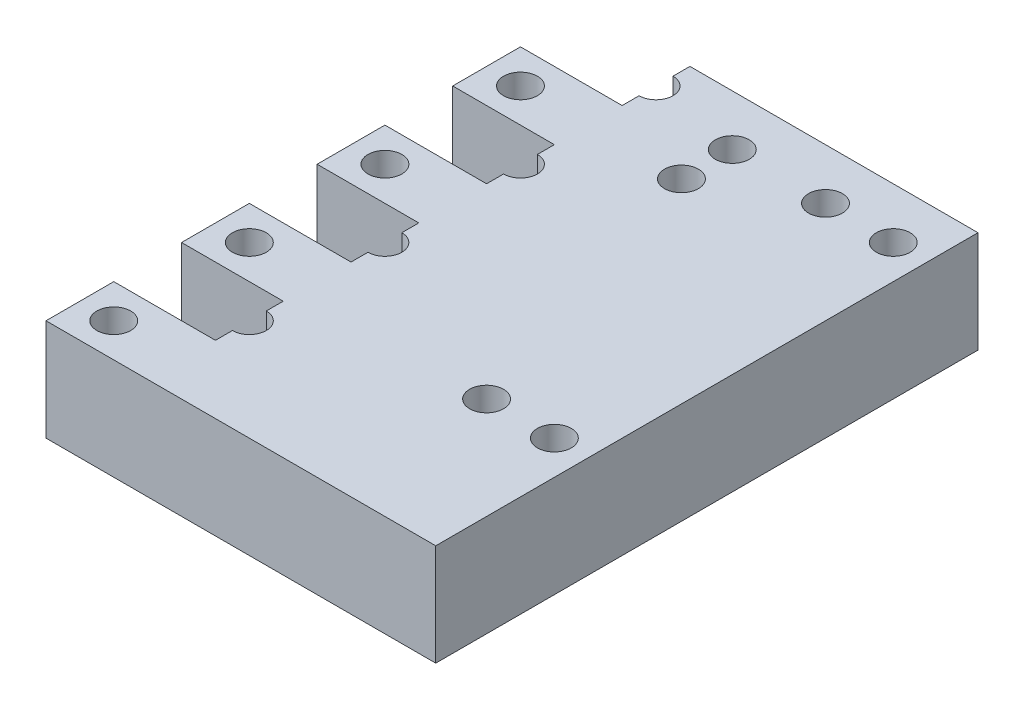
SolidWorks part; units mm, degrees
ref_plane "Front Plane" through (0, 0, 0) normal (0, 0, 1) x (1, 0, 0)
ref_plane "Top Plane" through (0, 0, 0) normal (0, 1, 0) x (1, 0, 0)
ref_plane "Right Plane" through (0, 0, 0) normal (1, 0, 0) x (0, 0, -1)
sketch "Sketch1" plane through (0, 0, 0) normal (0, 1, 0) x (1, 0, 0)
  line L0 (0, 0) -> (0, 4)
  line L1 (0, 4) -> (6, 4)
  line L2 (6, 4) -> (6, 8)
  line L3 (6, 8) -> (0, 8)
  line L4 (0, 8) -> (0, 12)
  line L5 (0, 12) -> (6, 12)
  line L6 (6, 12) -> (6, 16)
  line L7 (6, 16) -> (0, 16)
  line L8 (0, 16) -> (0, 20)
  line L9 (0, 20) -> (6, 20)
  line L10 (6, 20) -> (6, 24)
  line L11 (6, 24) -> (0, 24)
  line L12 (0, 24) -> (0, 28)
  line L13 (0, 28) -> (6, 28)
  line L14 (6, 28) -> (6, 32)
  line L15 (6, 32) -> (23, 32)
  line L16 (23, 32) -> (23, 0)
  line L17 (23, 0) -> (0, 0)
  dimension "D1" = 32
  dimension "D2" = 4
  dimension "D3" = 4
  dimension "D4" = 4
  dimension "D5" = 4
  dimension "D6" = 4
  dimension "D7" = 4
  dimension "D8" = 4
  dimension "D9" = 6
  dimension "D10" = 17
extrude "Boss-Extrude1" add sketch "Sketch1" along normal blind 6
sketch "Sketch2" plane through (0, 6, 0) normal (0, 1, 0) x (1, 0, 0)
  line L0 (0, 28) -> (0, 24) construction
  line L1 (0, 20) -> (0, 16) construction
  line L2 (0, 12) -> (0, 8) construction
  line L3 (0, 4) -> (0, 0) construction
  line L6 (6, 24) -> (6, 20) construction
  line L7 (6, 32) -> (6, 28) construction
  line L8 (6, 16) -> (6, 12) construction
  line L9 (6, 8) -> (6, 4) construction
  line L10 (23, 0) -> (23, 32) construction
  line L11 (0, 0) -> (23, 0) construction
  line L12 (23, 32) -> (6, 32) construction
  circle A0 centre (2, 26) radius 1
  circle A1 centre (2, 18) radius 1
  circle A2 centre (2, 10) radius 1
  circle A3 centre (2, 2) radius 1
  circle A4 centre (6, 22) radius 1
  circle A5 centre (6, 30) radius 1
  circle A6 centre (6, 14) radius 1
  circle A7 centre (6, 6) radius 1
  circle A8 centre (21, 29) radius 1
  circle A9 centre (21, 9) radius 1
  circle A10 centre (17, 29) radius 1
  circle A11 centre (17, 9) radius 1
  point P8 (0, 26)
  point P13 (0, 18)
  point P16 (0, 10)
  point P19 (0, 2)
  dimension "D1" = 2
  dimension "D3" = 2
  dimension "D2" = 2
  dimension "D4" = 2
  dimension "D5" = 9
  dimension "D6" = 3
  dimension "D7" = 4
extrude "Cut-Extrude1" cut sketch "Sketch2" against normal through all
sketch "Sketch3" plane through (0, 6, 0) normal (0, 1, 0) x (1, 0, 0)
  line L0 (23, 32) -> (6, 32) construction
  line L1 (6, 29) -> (6, 28) construction
  circle A0 centre (11.5, 29) radius 1
  circle A1 centre (11.5, 26) radius 1
  point P6 (6, 28.5)
  dimension "D1" = 2
  dimension "D2" = 3
  dimension "D3" = 3
  dimension "D4" = 5.5
extrude "Cut-Extrude2" cut sketch "Sketch3" against normal through all
